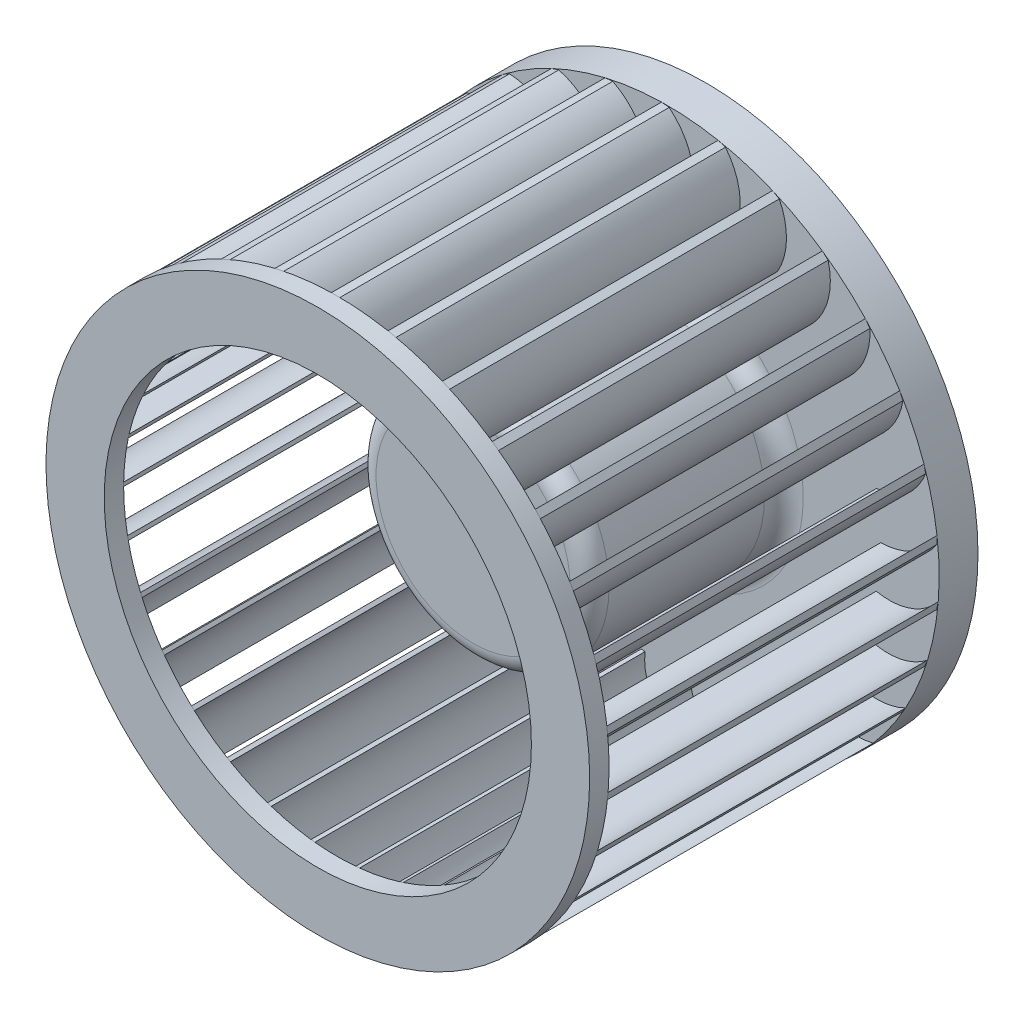
SolidWorks part; units mm, degrees
material "Silicon"
ref_plane "Front Plane" through (0, 0, 0) normal (0, 0, 1) x (1, 0, 0)
ref_plane "Top Plane" through (0, 0, 0) normal (0, 1, 0) x (1, 0, 0)
ref_plane "Right Plane" through (0, 0, 0) normal (1, 0, 0) x (0, 0, -1)
sketch "Sketch1" plane through (0, 0, 0) normal (0, 0, 1) x (1, 0, 0)
  circle A0 centre (0, 0) radius 14 construction
  dimension "D1" = 28
sketch "Sketch2" plane through (0, 0, 0) normal (0, 0, 1) x (1, 0, 0)
  circle A0 centre (0, 0) radius 14
  dimension "D1" = 28
extrude "Boss-Extrude1" add sketch "Sketch2" along normal blind 2
ref_plane "Plane1" through (0, 14, 0) normal (0, 1, 0) x (1, 0, 0)
ref_plane "Plane3" through (0, 13, 0) normal (0, 1, 0) x (1, 0, 0)
sketch "Sketch3" plane through (0, 13, 0) normal (0, 1, 0) x (1, 0, 0)
  line L0 (-14, -2) -> (14, -2) construction
  arc A0 (0, 0) -> (0, -2) centre (-36, -1) cw
  arc A1 (0, 0) -> (0, -2) centre (-54.9909, -1) cw
  dimension "D2" = 55
  dimension "D1" = 36
ref_plane "Plane2" through (0, 25, 0) normal (0, 1, 0) x (1, 0, 0)
sketch "Sketch4" plane through (0, 25, 0) normal (0, 1, 0) x (1, 0, 0)
  arc A0 (0, 0) -> (0, -2) centre (-32.2345, -1) cw
  arc A1 (0, 0) -> (0, -2) centre (-44.7388, -1) cw
  dimension "D1" = 32.25
  dimension "D2" = 44.75
sketch "Sketch5" plane through (0, 0, 2) normal (0, 0, 1) x (1, 0, 0)
  line L0 (0.0091, 13) -> (0, 13) construction
  line L1 (0, 0) -> (0, 13) construction
  line L2 (0, 13) -> (0, 14) construction
  line L3 (3.3352, 20.4911) -> (-3.3352, 5.5089) construction
  circle A0 centre (0, 0) radius 14 construction
  spline S0 degree 2 poles (0, 13) (1.6676, 16.7455) (0, 14) knots 0 0 0 1 1 1
  dimension "D1" = 8.2
  dimension "D2" = 24
sketch "Sketch6" plane through (0, 0, 0) normal (0, 0, -1) x (-1, 0, 0)
  circle A0 centre (0, 0) radius 14
  dimension "D1" = 28
sketch "Sketch7" plane through (0, 0, 2) normal (0, 0, 1) x (1, 0, 0)
  circle A0 centre (0, 0) radius 6
  dimension "D1" = 12
extrude "Boss-Extrude2" add sketch "Sketch7" along normal blind 10
sketch "Sketch8" plane through (0, 0, 2) normal (0, 0, 1) x (1, 0, 0)
  line L0 (0, 0) -> (14, 0) construction
  line L1 (13.8888, -1.7609) -> (13.8888, -1.3639) construction
  line L2 (11, -0.2) -> (11, 0.2) construction
  line L3 (13.8888, 1.7609) -> (13.8888, 1.3639)
  line L4 (11, 0) -> (11, -0.2)
  circle A0 centre (0, 0) radius 14 construction
  arc A1 (11, 0) -> (13.8888, -1.7609) centre (11, -3.25) cw construction
  arc A3 (11, 0.2) -> (13.8888, -1.3639) centre (11, -3.25) cw construction
  arc A4 (11, 0.2) -> (14.0666, -1.6693) centre (11, -3.25) cw construction
  arc A5 (11, 0) -> (13.8888, 1.7609) centre (11, 3.25) ccw
  arc A6 (11, -0.2) -> (13.8888, 1.3639) centre (11, 3.25) ccw
  dimension "D1" = 3.25
  dimension "D2" = 11
  dimension "D3" = 0.2
extrude "Boss-Extrude3" add sketch "Sketch8" along normal blind 17
pattern_circular "CirPattern1" count 30 over 360 about axis through (0, 0, 0) along (0, 0, 1) of "Boss-Extrude3"
sketch "Sketch9" plane through (0, 0, 19) normal (0, 0, 1) x (1, 0, 0)
  circle A0 centre (0, 0) radius 14
  circle A1 centre (0, 0) radius 14 construction
  circle A2 centre (0, 0) radius 11
extrude "Boss-Extrude4" add sketch "Sketch9" along normal blind 1
fillet "Fillet2" radius 1 2 edges at (6, 0, 12) (6, 0, 2)
